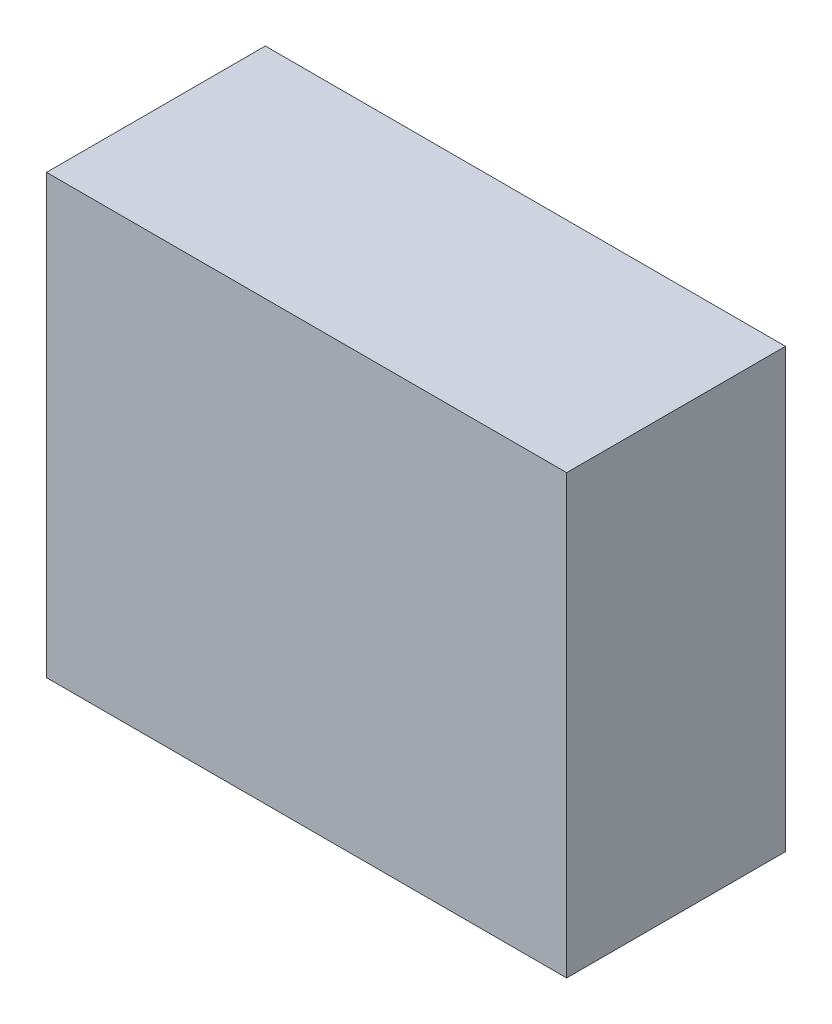
SolidWorks part; units mm, degrees
ref_plane "正面" through (0, 0, 0) normal (1, 0, 0) x (0, 1, 0)
ref_plane "平面" through (0, 0, 0) normal (0, 0, 1) x (0, 1, 0)
ref_plane "右側面" through (0, 0, 0) normal (0, 1, 0) x (-1, 0, 0)
sketch "ｽｹｯﾁ1" plane through (0, 0, 0) normal (1, 0, 0) x (0, 1, 0)
  line L1 (-6.1, -3.05) -> (6.1, -3.05)
  line L2 (-6.1, -3.05) -> (-6.1, 3.05)
  line L3 (-6.1, 3.05) -> (6.1, 3.05)
  line L4 (6.1, -3.05) -> (6.1, 3.05)
  line L5 (-6.1, -3.05) -> (6.1, 3.05) construction
  line L6 (-6.1, 3.05) -> (6.1, -3.05) construction
  point P0 (0, 0)
  dimension "D1" = 6.1
  dimension "D2" = 12.2
extrude "ﾎﾞｽ - 押し出し1" add sketch "ｽｹｯﾁ1" along normal blind 14.5
